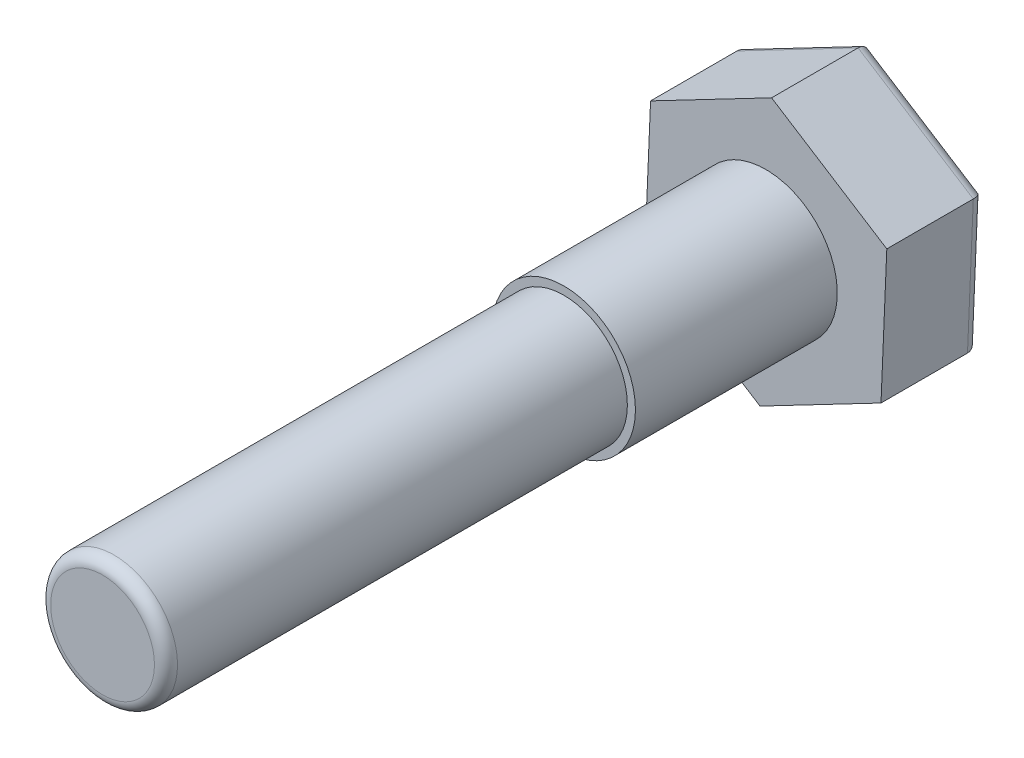
SolidWorks part; units mm, degrees
ref_plane "前视" through (0, 0, 0) normal (0, 0, 1) x (1, 0, 0)
ref_plane "上视" through (0, 0, 0) normal (0, 1, 0) x (1, 0, 0)
ref_plane "右视" through (0, 0, 0) normal (1, 0, 0) x (0, 0, -1)
sketch "草图1" plane through (0, 0, 0) normal (0, 0, 1) x (1, 0, 0)
  line L1 (20.9842, 10.9543) -> (1.0054, 23.65)
  line L2 (1.0054, 23.65) -> (-19.9788, 12.6957)
  line L3 (-19.9788, 12.6957) -> (-20.9842, -10.9543)
  line L4 (-20.9842, -10.9543) -> (-1.0054, -23.65)
  line L5 (-1.0054, -23.65) -> (19.9788, -12.6957)
  line L6 (19.9788, -12.6957) -> (20.9842, 10.9543)
  circle A0 centre (0, 0) radius 20.5 construction
  dimension "D1" = 47.3
  dimension "D2" = 41
extrude "基体-拉伸" add sketch "草图1" along normal blind 17
sketch "草图2" plane through (0, 0, 17) normal (0, 0, 1) x (1, 0, 0)
  circle A0 centre (0, 0) radius 12.4
  dimension "D1" = 24.8
extrude "凸台-拉伸1" add sketch "草图2" along normal blind 35
fillet "圆角3" radius 2 6 edges at (9.4867, -18.1729, 0) (-10.9948, -17.3021, 0) (-20.4815, 0.8707, 0) (-9.4867, 18.1729, 0) (10.9948, 17.3021, 0) (20.4815, -0.8707, 0)
sketch "草图3" plane through (0, 0, 52) normal (0, 0, 1) x (1, 0, 0)
  circle A0 centre (0, 0) radius 11
  dimension "D1" = 22
extrude "凸台-拉伸2" add sketch "草图3" along normal blind 80
fillet "圆角4" radius 2 1 edges at (11, 0, 132)
